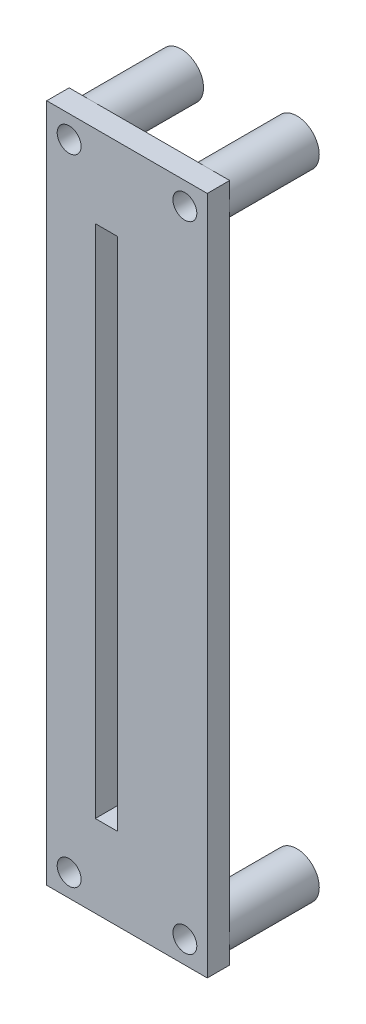
SolidWorks part; units mm, degrees
ref_plane "Front Plane" through (0, 0, 0) normal (0, 0, 1) x (1, 0, 0)
ref_plane "Top Plane" through (0, 0, 0) normal (0, 1, 0) x (1, 0, 0)
ref_plane "Right Plane" through (0, 0, 0) normal (1, 0, 0) x (0, 0, -1)
sketch "Sketch1" plane through (0, 0, 0) normal (0, 0, 1) x (1, 0, 0)
  line L0 (3, 88) -> (3, 3) construction
  line L1 (0, 0) -> (21.5, 0)
  line L2 (0, 0) -> (0, 91)
  line L3 (0, 91) -> (21.5, 91)
  line L4 (21.5, 0) -> (21.5, 91)
  line L5 (10.75, 91) -> (10.75, 0) construction
  line L6 (0, 45.5) -> (21.5, 45.5) construction
  line L7 (3, 3) -> (18.5, 3) construction
  line L8 (18.5, 3) -> (18.5, 88) construction
  line L9 (18.5, 88) -> (3, 88) construction
  line L11 (6.5, 80) -> (9.5, 80)
  line L12 (6.5, 80) -> (6.5, 11)
  line L13 (6.5, 11) -> (9.5, 11)
  line L14 (9.5, 80) -> (9.5, 11)
  line L15 (8, 11) -> (8, 80) construction
  line L16 (6.5, 45.5) -> (9.5, 45.5) construction
  circle A0 centre (3, 88) radius 1.6
  circle A1 centre (18.5, 88) radius 1.6
  circle A2 centre (3, 3) radius 1.6
  circle A3 centre (18.5, 3) radius 1.6
  point P532 (8, 45.5)
  point P1064 (10.75, 45.5)
  dimension "D3" = 3.2
  dimension "D4" = 3.2
  dimension "D5" = 3.2
  dimension "D6" = 3.2
  dimension "D1" = 85
  dimension "D2" = 15.5
  dimension "D7" = 3
  dimension "D8" = 3
  dimension "D9" = 3
  dimension "D10" = 3
  dimension "D11" = 69
  dimension "D12" = 5
  dimension "D13" = 3
extrude "Boss-Extrude1" add sketch "Sketch1" along normal blind 3
sketch "Sketch2" plane through (0, 0, 0) normal (0, 0, 1) x (1, 0, 0)
  circle A0 centre (3, 88) radius 1.6
  circle A1 centre (18.5, 88) radius 1.6
  circle A2 centre (18.5, 3) radius 1.6
  circle A3 centre (3, 3) radius 1.6
  circle A4 centre (3, 3) radius 3
  circle A5 centre (18.5, 3) radius 3
  circle A6 centre (18.5, 88) radius 3
  circle A7 centre (3, 88) radius 3
extrude "Boss-Extrude2" add sketch "Sketch2" against normal blind 12
